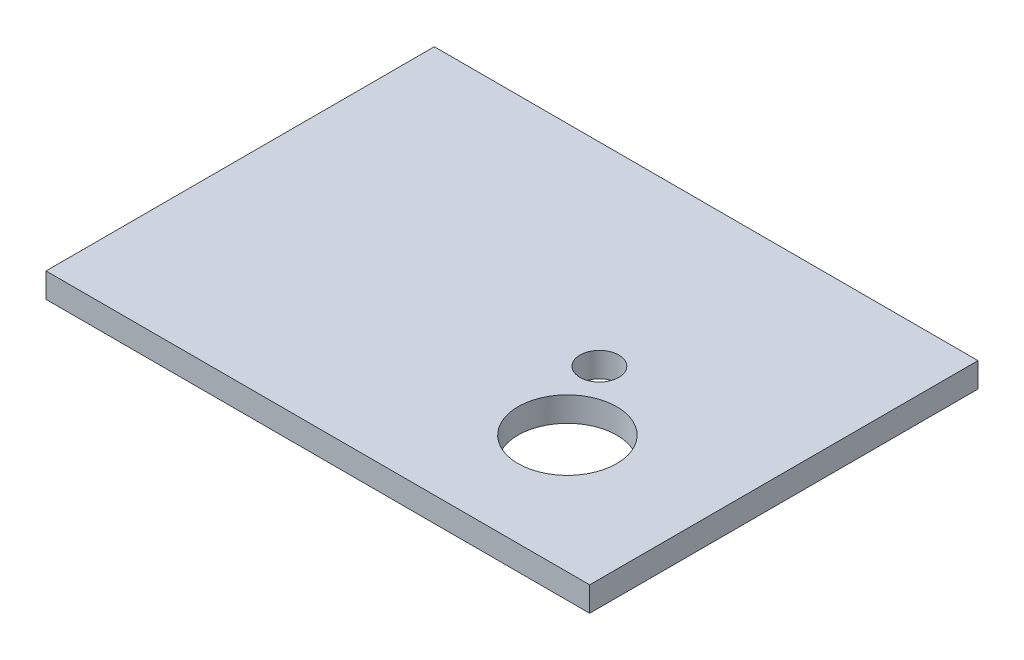
SolidWorks part; units mm, degrees
material "Oak"
ref_plane "Front Plane" through (0, 0, 0) normal (0, 0, 1) x (1, 0, 0)
ref_plane "Top Plane" through (0, 0, 0) normal (0, 1, 0) x (1, 0, 0)
ref_plane "Right Plane" through (0, 0, 0) normal (1, 0, 0) x (0, 0, -1)
sketch "Sketch1" plane through (0, 0, 0) normal (0, 1, 0) x (1, 0, 0)
  line L1 (0, 0) -> (140, 0)
  line L2 (0, 0) -> (0, 100)
  line L3 (0, 100) -> (140, 100)
  line L4 (140, 0) -> (140, 100)
  dimension "D1" = 140
  dimension "D2" = 100
extrude "Boss-Extrude1" add sketch "Sketch1" along normal blind 6.35
sketch "Sketch2" plane through (0, 6.35, 0) normal (0, 1, 0) x (1, 0, 0)
  line L0 (0, 50) -> (140, 50) construction
  line L1 (0, 100) -> (0, 0) construction
  line L2 (140, 0) -> (140, 100) construction
  line L3 (70, 100) -> (70, 0) construction
  line L4 (140, 100) -> (0, 100) construction
  line L5 (0, 0) -> (140, 0) construction
  line L6 (92.5, 50) -> (114.578, 11.7597) construction
  circle A0 centre (103.75, 30.5144) radius 12.705
  circle A1 centre (92.5, 50) radius 5
  point P12 (92.5, 50)
  point P13 (70, 50)
  dimension "D3" = 25.41
  dimension "D5" = 10
  dimension "D1" = 22.5
  dimension "D2" = 120
  dimension "D4" = 22.5
  dimension "D6" = 30.5144
  dimension "D7" = 36.25
extrude "Cut-Extrude1" cut sketch "Sketch2" against normal blind 10
